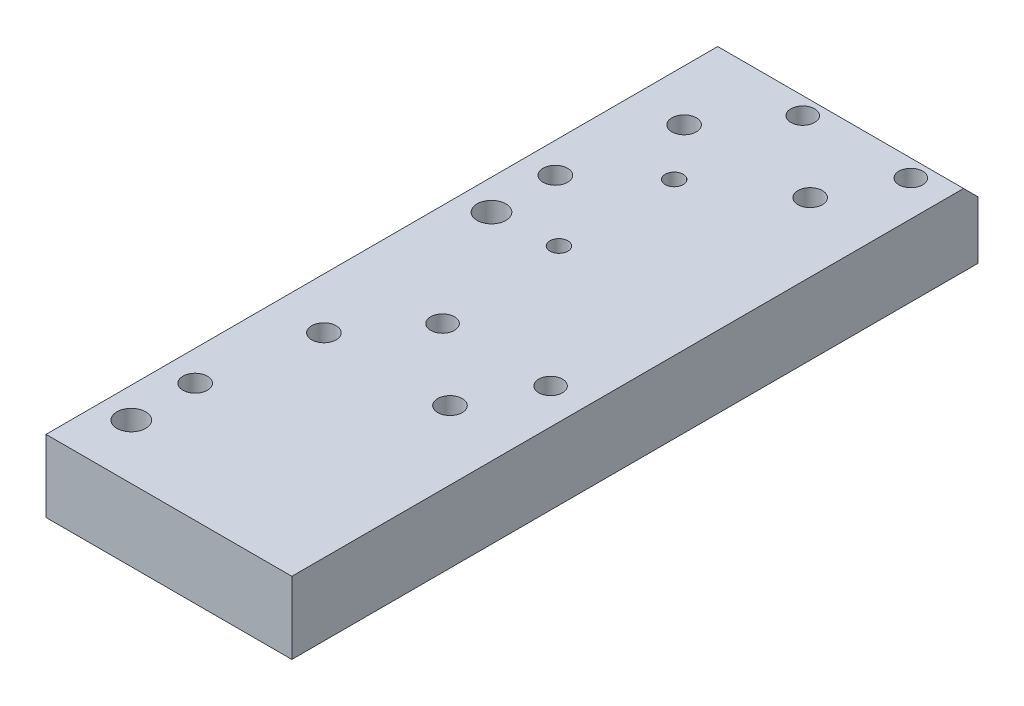
SolidWorks part; units mm, degrees
material "Low Carbon Steel"
ref_plane "Front Plane" through (0, 0, 0) normal (0, 0, 1) x (1, 0, 0)
ref_plane "Top Plane" through (0, 0, 0) normal (0, 1, 0) x (1, 0, 0)
ref_plane "Right Plane" through (0, 0, 0) normal (1, 0, 0) x (0, 0, -1)
sketch "Sketch1" plane through (0, 0, 0) normal (0, 1, 0) x (1, 0, 0)
  line L1 (0, 95.25) -> (-68.2625, 95.25)
  line L2 (0, 95.25) -> (0, -95.25)
  line L3 (0, -95.25) -> (-68.2625, -95.25)
  line L4 (-68.2625, 95.25) -> (-68.2625, -95.25)
  dimension "D1" = 190.5
  dimension "D2" = 68.2625
extrude "Boss-Extrude1" add sketch "Sketch1" along normal blind 20
chamfer "Chamfer1" distance 4 angle 45 1 edges at (-34.1312, 20, -95.25)
hole_wizard "M8 Tapped Hole1" positions "Sketch2" profile "Sketch3" tap size "M8" standard "Peddi DIN" end condition through all
sketch "Sketch2" plane through (0, 20, 0) normal (0, 1, 0) x (1, 0, 0)
  line L1 (-68.2625, 91.25) -> (-68.2625, -95.25) construction
  line L2 (-68.2625, -95.25) -> (0, -95.25) construction
  point P0 (-59.85, -62.25)
  point P2 (-54.1, -32.25)
  point P4 (-19.1, -32.25)
  point P6 (-59.85, 37.75)
  point P8 (-54.1, 67.75)
  point P10 (-19.1, 67.75)
  dimension "D1" = 30
  dimension "D2" = 35
  dimension "D3" = 5.75
  dimension "D4" = 100
  dimension "D5" = 33
  dimension "D6" = 8.4125
  dimension "D7" = 100
cosmetic thread "Hole Thread1" parameters "D2"=8
cosmetic thread "Hole Thread2" parameters "D2"=8
cosmetic thread "Hole Thread3" parameters "D2"=8
cosmetic thread "Hole Thread4" parameters "D2"=8
cosmetic thread "Hole Thread5" parameters "D2"=8
cosmetic thread "Hole Thread6" parameters "D2"=8
sketch "Sketch3" plane through (-59.85, 20, 62.25) normal (1, 0, 0) x (0, 0, 1)
  line L0 (0, 0) -> (0, 20)
  line L1 (0, 20) -> (3.4, 20)
  line L2 (3.4, 20) -> (3.4, 0)
  line L5 (3.4, 0) -> (0, 0)
  line L11 (0, -6.35) -> (0, 107.95) construction
  dimension "Thru Tap Drill Dia." = 6.8
  dimension "Thru Tap Drill Depth" = 20
hole_wizard "Ø8.0 (8) Diameter Hole1" positions "Sketch4" profile "Sketch5" hole size "Ø8.0" standard "Peddi DIN" end condition through all
sketch "Sketch4" plane through (0, 20, 0) normal (0, 1, 0) x (1, 0, 0)
  line L0 (-59.85, 37.75) -> (-59.85, 20.0208) construction
  line L2 (-59.85, -62.25) -> (-59.85, -79.9792) construction
  circle A0 centre (-59.85, 37.75) radius 3.4 construction
  point P0 (-59.85, 20.0208)
  point P2 (-59.85, -79.9792)
  dimension "D1" = 17.7292
sketch "Sketch5" plane through (-59.85, 20, -20.0208) normal (1, 0, 0) x (0, 0, 1)
  line L0 (0, 0) -> (0, 20)
  line L1 (0, 20) -> (4, 20)
  line L2 (4, 20) -> (4, 0)
  line L5 (4, 0) -> (0, 0)
  line L11 (0, -6.35) -> (0, 107.95) construction
  dimension "Thru Hole Dia." = 8
  dimension "Thru Hole Depth" = 20
sketch "Sketch6" plane through (0, 0, 0) normal (0, -1, 0) x (1, 0, 0)
  line L0 (-68.2625, 79.9792) -> (-54.85, 79.9792) construction
  line L1 (-68.2625, -95.25) -> (-68.2625, 95.25) construction
  line L2 (-68.2625, 85.1242) -> (-54.85, 85.1242)
  line L3 (-68.2625, 74.8342) -> (-54.85, 74.8342)
  line L4 (-68.2625, -20.0208) -> (-54.85, -20.0208) construction
  line L5 (-68.2625, -14.8758) -> (-54.85, -14.8758)
  line L6 (-68.2625, -25.1658) -> (-54.85, -25.1658)
  arc A0 (-68.2625, 85.1242) -> (-68.2625, 74.8342) centre (-68.2625, 79.9792) ccw
  arc A1 (-54.85, 74.8342) -> (-54.85, 85.1242) centre (-54.85, 79.9792) ccw
  arc A2 (-68.2625, -14.8758) -> (-68.2625, -25.1658) centre (-68.2625, -20.0208) ccw
  arc A3 (-54.85, -25.1658) -> (-54.85, -14.8758) centre (-54.85, -20.0208) ccw
  circle A5 centre (-59.85, -20.0208) radius 4 construction
  point P4 (-61.5562, 79.9792)
  point P9 (-61.5562, -20.0208)
  point P16 (-59.85, -20.0208)
  point P19 (-59.85, 79.9792)
  dimension "D1" = 5
  dimension "D2" = 10.29
extrude "Cut-Extrude1" cut sketch "Sketch6" against normal blind 11
fillet "Fillet1" radius 0.254 6 edges at (-61.5562, 11, -14.8758) (-49.705, 11, -20.0208) (-61.5562, 11, 85.1242) (-49.705, 11, 79.9792) (-61.5562, 11, -25.1658) (-61.5562, 11, 74.8342)
hole_wizard "CBORE for M6 Hex Socket Head Cap Screw1" positions "Sketch7" profile "Sketch8" counterbore size "M6" standard "Peddi DIN" end condition through all
sketch "Sketch7" plane through (0, 0, 0) normal (0, -1, 0) x (-1, 0, 0)
  line L0 (0, -95.25) -> (0, 95.25) construction
  circle A0 centre (19.1, -32.25) radius 3.4 construction
  point P0 (9.85, 86.4348)
  point P2 (39.85, 86.4348)
  point P4 (39.85, -13.5652)
  point P6 (9.85, -13.5652)
  dimension "D1" = 9.85
  dimension "D2" = 18.6848
  dimension "D3" = 30
  dimension "D4" = 100
sketch "Sketch8" plane through (-9.85, 0, -86.4348) normal (1, 0, 0) x (0, 0, -1)
  line L0 (0, 0) -> (0, 20)
  line L1 (0, 20) -> (3.3, 20)
  line L3 (3.3, 20) -> (3.3, 7)
  line L4 (3.3, 7) -> (5.5, 7)
  line L5 (5.5, 7) -> (5.5, 0)
  line L7 (5.5, 0) -> (0, 0)
  line L11 (0, -6.35) -> (0, 107.95) construction
  dimension "Thru Hole Dia." = 6.6
  dimension "Thru Hole Depth" = 20
  dimension "C'Bore Dia." = 11
  dimension "C'Bore Depth" = 7
hole_wizard "M6 Tapped Hole1" positions "Sketch9" profile "Sketch10" tap size "M6" standard "Peddi DIN"
sketch "Sketch9" plane through (0, 0, 0) normal (0, -1, 0) x (-1, 0, 0)
  circle A0 centre (59.85, 37.75) radius 3.4 construction
  point P0 (42.35, 21.25)
  point P2 (42.35, 53.25)
  dimension "D2" = 16.5
  dimension "D3" = 17.5
  dimension "D1" = 32
sketch "Sketch10" plane through (-42.35, 0, -21.25) normal (1, 0, 0) x (0, 0, -1)
  line L0 (0, 0) -> (0, 29.493)
  line L1 (0, 29.493) -> (2.5, 27.9908)
  line L2 (2.5, 27.9908) -> (2.5, 0)
  line L5 (2.5, 0) -> (0, 0)
  line L10 (0, 29.493) -> (-2.5, 27.9908) construction
  line L11 (0, -6.35) -> (0, 107.95) construction
  dimension "Tap Drill Dia." = 5
  dimension "Tap Drill Depth" = 27.9908
  dimension "Drill Angle" = 118
cosmetic thread "Hole Thread7" parameters "D1"=15.0114, "D2"=6
cosmetic thread "Hole Thread8" parameters "D1"=15.0114, "D2"=6
other "Freeze***"
